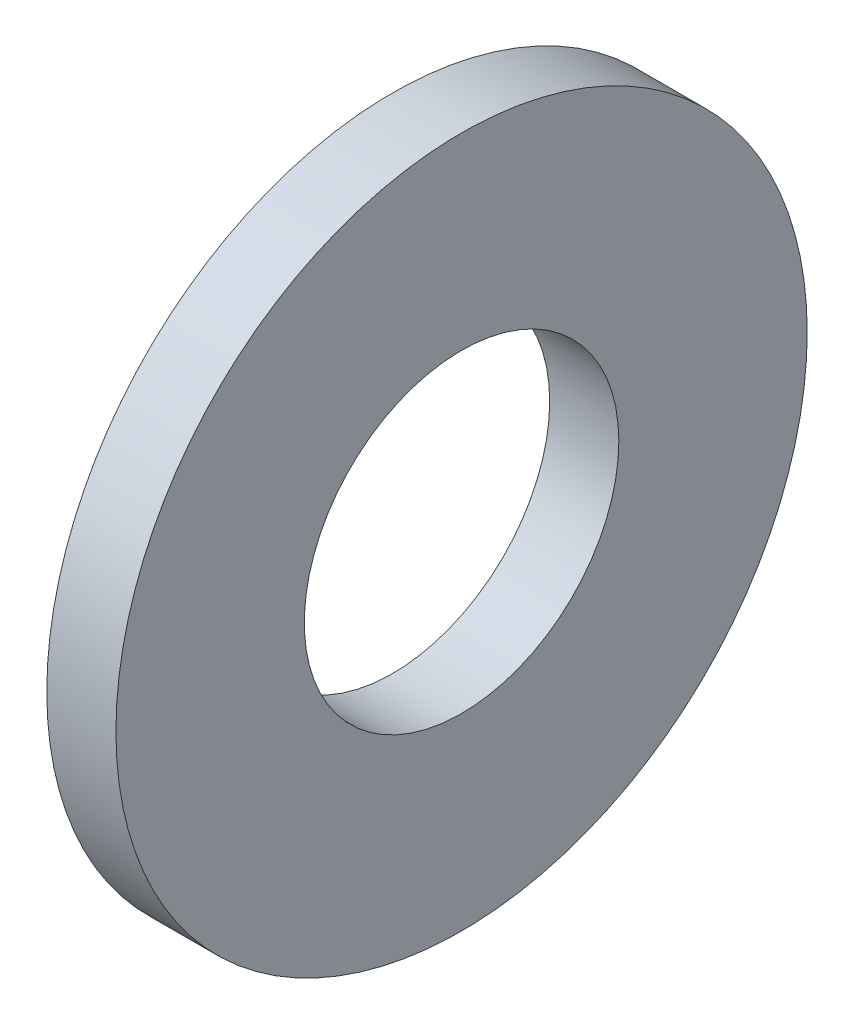
SolidWorks part; units mm, degrees
ref_plane "Plane1" through (0, 0, 0) normal (0, 0, 1) x (1, 0, 0)
ref_plane "Plane2" through (0, 0, 0) normal (0, 1, 0) x (1, 0, 0)
ref_plane "Plane3" through (0, 0, 0) normal (1, 0, 0) x (0, 0, -1)
other "Configuration Table"
sketch "Sketch1" plane through (0, 0, 0) normal (1, 0, 0) x (0, 0, -1)
  circle A0 centre (0, 0) radius 2.275
  circle A1 centre (0, 0) radius 5
  dimension "Insid_dia" = 4.55
  dimension "OutsideDia" = 10
extrude "Base-Extrude" add sketch "Sketch1" along normal blind 1
